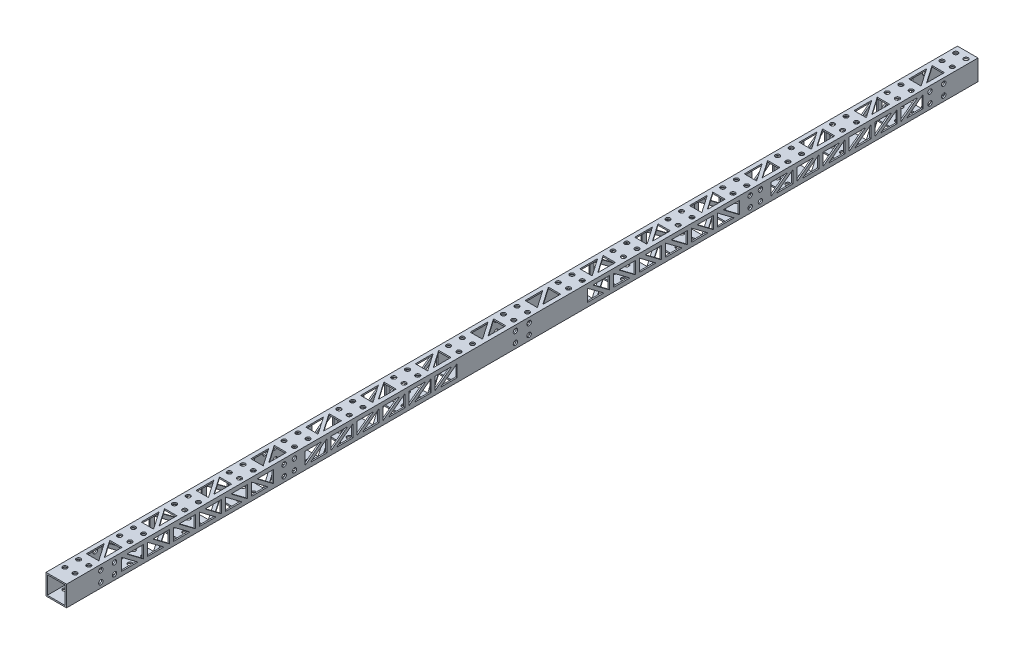
SolidWorks part; units mm, degrees
ref_plane "前视基准面" through (0, 0, 0) normal (0, 0, 1) x (1, 0, 0)
ref_plane "上视基准面" through (0, 0, 0) normal (0, 1, 0) x (1, 0, 0)
ref_plane "右视基准面" through (0, 0, 0) normal (1, 0, 0) x (0, 0, -1)
other "Configuration Table"
sketch "草图1" plane through (0, 0, 0) normal (0, 0, 1) x (1, 0, 0)
  line L1 (0, 0) -> (15, 0)
  line L2 (0, 0) -> (0, -15)
  line L3 (0, -15) -> (15, -15)
  line L4 (15, 0) -> (15, -15)
  dimension "D1" = 15
  dimension "D2" = 15
extrude "拉伸-薄壁1" add sketch "草图1" along normal blind 665 thin
sketch "草图2" plane through (15, 0, 0) normal (1, 0, 0) x (0, 0, -1)
  line L0 (-332.5, 0) -> (-332.5, -15) construction
  line L1 (-665, 0) -> (0, 0) construction
  line L2 (-665, -15) -> (0, -15) construction
  line L3 (-635, 0) -> (-635, -15) construction
  line L4 (-665, -15) -> (-665, 0) construction
  line L5 (-665, -7.5) -> (-635, -7.5) construction
  line L6 (-30, 0) -> (-30, -15) construction
  line L7 (0, -7.5) -> (-30, -7.5) construction
  line L8 (0, -15) -> (0, 0) construction
  line L9 (-635, -7.5) -> (0, -7.5) construction
  line L10 (-502.5, 0) -> (-502.5, -15) construction
  line L11 (-162.5, 0) -> (-162.5, -15) construction
  line L12 (-625, -3) -> (-625, -12)
  line L13 (-625, -12) -> (-613, -12)
  line L14 (-613, -12) -> (-625, -3)
  line L18 (-621, -3) -> (-609, -3)
  line L19 (-609, -3) -> (-609, -12)
  line L20 (-609, -12) -> (-621, -3)
  line L21 (-606, -3) -> (-606, -12)
  line L22 (-594, -12) -> (-606, -3)
  line L23 (-606, -12) -> (-594, -12)
  line L24 (-590, -12) -> (-602, -3)
  line L25 (-602, -3) -> (-590, -3)
  line L26 (-590, -3) -> (-590, -12)
  line L27 (-587, -3) -> (-587, -12)
  line L28 (-575, -12) -> (-587, -3)
  line L29 (-587, -12) -> (-575, -12)
  line L30 (-571, -12) -> (-583, -3)
  line L31 (-583, -3) -> (-571, -3)
  line L32 (-571, -3) -> (-571, -12)
  line L33 (-568, -3) -> (-568, -12)
  line L34 (-556, -12) -> (-568, -3)
  line L35 (-568, -12) -> (-556, -12)
  line L36 (-552, -12) -> (-564, -3)
  line L37 (-564, -3) -> (-552, -3)
  line L38 (-552, -3) -> (-552, -12)
  line L39 (-549, -3) -> (-549, -12)
  line L40 (-537, -12) -> (-549, -3)
  line L41 (-549, -12) -> (-537, -12)
  line L42 (-533, -12) -> (-545, -3)
  line L43 (-545, -3) -> (-533, -3)
  line L44 (-533, -3) -> (-533, -12)
  line L45 (-530, -3) -> (-530, -12)
  line L46 (-518, -12) -> (-530, -3)
  line L47 (-530, -12) -> (-518, -12)
  line L48 (-514, -12) -> (-526, -3)
  line L49 (-526, -3) -> (-514, -3)
  line L50 (-514, -3) -> (-514, -12)
  line L51 (-491, -3) -> (-491, -12)
  line L52 (-479, -3) -> (-491, -3)
  line L53 (-491, -12) -> (-479, -3)
  line L54 (-475, -12) -> (-487, -12)
  line L55 (-487, -12) -> (-475, -3)
  line L56 (-475, -3) -> (-475, -12)
  line L57 (-472, -3) -> (-472, -12)
  line L58 (-460, -3) -> (-472, -3)
  line L59 (-472, -12) -> (-460, -3)
  line L60 (-456, -12) -> (-468, -12)
  line L61 (-468, -12) -> (-456, -3)
  line L62 (-456, -3) -> (-456, -12)
  line L63 (-453, -3) -> (-453, -12)
  line L64 (-441, -3) -> (-453, -3)
  line L65 (-453, -12) -> (-441, -3)
  line L66 (-437, -12) -> (-449, -12)
  line L67 (-449, -12) -> (-437, -3)
  line L68 (-437, -3) -> (-437, -12)
  line L69 (-434, -3) -> (-434, -12)
  line L70 (-422, -3) -> (-434, -3)
  line L71 (-434, -12) -> (-422, -3)
  line L72 (-418, -12) -> (-430, -12)
  line L73 (-430, -12) -> (-418, -3)
  line L74 (-418, -3) -> (-418, -12)
  line L75 (-415, -3) -> (-415, -12)
  line L76 (-403, -3) -> (-415, -3)
  line L77 (-415, -12) -> (-403, -3)
  line L78 (-399, -12) -> (-411, -12)
  line L79 (-411, -12) -> (-399, -3)
  line L80 (-399, -3) -> (-399, -12)
  line L81 (-396, -12) -> (-384, -3)
  line L82 (-396, -3) -> (-396, -12)
  line L83 (-384, -3) -> (-396, -3)
  line L84 (-392, -12) -> (-380, -3)
  line L85 (-380, -12) -> (-392, -12)
  line L86 (-380, -3) -> (-380, -12)
  line L87 (-285, -3) -> (-285, -12)
  line L88 (-285, -12) -> (-273, -12)
  line L89 (-273, -12) -> (-285, -3)
  line L90 (-281, -3) -> (-269, -3)
  line L91 (-269, -3) -> (-269, -12)
  line L92 (-269, -12) -> (-281, -3)
  line L93 (-266, -3) -> (-266, -12)
  line L94 (-254, -12) -> (-266, -3)
  line L95 (-266, -12) -> (-254, -12)
  line L96 (-250, -12) -> (-262, -3)
  line L97 (-262, -3) -> (-250, -3)
  line L98 (-250, -3) -> (-250, -12)
  line L99 (-247, -3) -> (-247, -12)
  line L100 (-235, -12) -> (-247, -3)
  line L101 (-247, -12) -> (-235, -12)
  line L102 (-231, -12) -> (-243, -3)
  line L103 (-243, -3) -> (-231, -3)
  line L104 (-231, -3) -> (-231, -12)
  line L105 (-228, -3) -> (-228, -12)
  line L106 (-216, -12) -> (-228, -3)
  line L107 (-228, -12) -> (-216, -12)
  line L108 (-212, -12) -> (-224, -3)
  line L109 (-224, -3) -> (-212, -3)
  line L110 (-212, -3) -> (-212, -12)
  line L111 (-209, -3) -> (-209, -12)
  line L112 (-197, -12) -> (-209, -3)
  line L113 (-209, -12) -> (-197, -12)
  line L114 (-193, -12) -> (-205, -3)
  line L115 (-205, -3) -> (-193, -3)
  line L116 (-193, -3) -> (-193, -12)
  line L117 (-190, -3) -> (-190, -12)
  line L118 (-178, -12) -> (-190, -3)
  line L119 (-190, -12) -> (-178, -12)
  line L120 (-174, -12) -> (-186, -3)
  line L121 (-186, -3) -> (-174, -3)
  line L122 (-174, -3) -> (-174, -12)
  line L123 (-151, -3) -> (-151, -12)
  line L124 (-139, -3) -> (-151, -3)
  line L125 (-151, -12) -> (-139, -3)
  line L126 (-135, -12) -> (-147, -12)
  line L127 (-147, -12) -> (-135, -3)
  line L128 (-135, -3) -> (-135, -12)
  line L129 (-132, -3) -> (-132, -12)
  line L130 (-120, -3) -> (-132, -3)
  line L131 (-132, -12) -> (-120, -3)
  line L132 (-116, -12) -> (-128, -12)
  line L133 (-128, -12) -> (-116, -3)
  line L134 (-116, -3) -> (-116, -12)
  line L135 (-113, -3) -> (-113, -12)
  line L136 (-101, -3) -> (-113, -3)
  line L137 (-113, -12) -> (-101, -3)
  line L138 (-97, -12) -> (-109, -12)
  line L139 (-109, -12) -> (-97, -3)
  line L140 (-97, -3) -> (-97, -12)
  line L141 (-94, -3) -> (-94, -12)
  line L142 (-82, -3) -> (-94, -3)
  line L143 (-94, -12) -> (-82, -3)
  line L144 (-78, -12) -> (-90, -12)
  line L145 (-90, -12) -> (-78, -3)
  line L146 (-78, -3) -> (-78, -12)
  line L147 (-75, -3) -> (-75, -12)
  line L148 (-63, -3) -> (-75, -3)
  line L149 (-75, -12) -> (-63, -3)
  line L150 (-59, -12) -> (-71, -12)
  line L151 (-71, -12) -> (-59, -3)
  line L152 (-59, -3) -> (-59, -12)
  line L153 (-56, -12) -> (-44, -3)
  line L154 (-56, -3) -> (-56, -12)
  line L155 (-44, -3) -> (-56, -3)
  line L156 (-52, -12) -> (-40, -3)
  line L157 (-40, -12) -> (-52, -12)
  line L158 (-40, -3) -> (-40, -12)
  circle A0 centre (-640, -3.75) radius 1.6
  circle A1 centre (-640, -11.25) radius 1.6
  circle A2 centre (-630, -11.25) radius 1.6
  circle A3 centre (-630, -3.75) radius 1.6
  circle A8 centre (-25, -3.75) radius 1.6
  circle A9 centre (-25, -11.25) radius 1.6
  circle A10 centre (-35, -11.25) radius 1.6
  circle A11 centre (-35, -3.75) radius 1.6
  circle A12 centre (-337.5, -3.75) radius 1.6
  circle A13 centre (-337.5, -11.25) radius 1.6
  circle A14 centre (-327.5, -11.25) radius 1.6
  circle A15 centre (-327.5, -3.75) radius 1.6
  circle A16 centre (-506.25, -3.75) radius 1.6
  circle A17 centre (-506.25, -11.25) radius 1.6
  circle A18 centre (-498.75, -11.25) radius 1.6
  circle A19 centre (-498.75, -3.75) radius 1.6
  circle A20 centre (-166.25, -3.75) radius 1.6
  circle A21 centre (-166.25, -11.25) radius 1.6
  circle A22 centre (-158.75, -11.25) radius 1.6
  circle A23 centre (-158.75, -3.75) radius 1.6
  dimension "D2" = 3.2
  dimension "D6" = 3.2
  dimension "D9" = 3.2
  dimension "D13" = 3.2
  dimension "D1" = 30
  dimension "D3" = 5
  dimension "D4" = 3.75
  dimension "D5" = 30
  dimension "D7" = 3.75
  dimension "D8" = 5
  dimension "D10" = 5
  dimension "D11" = 3.75
  dimension "D12" = 162.5
  dimension "D14" = 3.75
  dimension "D15" = 3.75
  dimension "D16" = 9
  dimension "D17" = 12
  dimension "D18" = 10
  dimension "D19" = 9
  dimension "D20" = 12
  dimension "D21" = 16
  dimension "D23" = 19
  dimension "D22" = 6
extrude "切除-拉伸1" cut sketch "草图2" against normal through all
sketch "草图3" plane through (0, 0, 0) normal (0, 1, 0) x (1, 0, 0)
  line L0 (0, -10) -> (15, -10) construction
  line L1 (0, -665) -> (0, 0) construction
  line L2 (15, -665) -> (15, 0) construction
  line L3 (7.5, 0) -> (7.5, -10) construction
  line L4 (15, 0) -> (0, 0) construction
  line L6 (3, -21.5) -> (12, -21.5)
  line L7 (12, -21.5) -> (12, -34.5)
  line L8 (12, -34.5) -> (3, -21.5)
  line L9 (3, -25.5) -> (3, -38.5)
  line L10 (3, -38.5) -> (12, -38.5)
  line L11 (12, -38.5) -> (3, -25.5)
  line L12 (3, -61.5) -> (12, -61.5)
  line L13 (12, -61.5) -> (12, -74.5)
  line L14 (12, -74.5) -> (3, -61.5)
  line L15 (12, -78.5) -> (3, -65.5)
  line L16 (3, -65.5) -> (3, -78.5)
  line L17 (3, -78.5) -> (12, -78.5)
  line L18 (3, -101.5) -> (12, -101.5)
  line L19 (12, -101.5) -> (12, -114.5)
  line L20 (12, -114.5) -> (3, -101.5)
  line L21 (12, -118.5) -> (3, -105.5)
  line L22 (3, -105.5) -> (3, -118.5)
  line L23 (3, -118.5) -> (12, -118.5)
  line L24 (3, -141.5) -> (12, -141.5)
  line L25 (12, -141.5) -> (12, -154.5)
  line L26 (12, -154.5) -> (3, -141.5)
  line L27 (12, -158.5) -> (3, -145.5)
  line L28 (3, -145.5) -> (3, -158.5)
  line L29 (3, -158.5) -> (12, -158.5)
  line L30 (3, -181.5) -> (12, -181.5)
  line L31 (12, -181.5) -> (12, -194.5)
  line L32 (12, -194.5) -> (3, -181.5)
  line L33 (12, -198.5) -> (3, -185.5)
  line L34 (3, -185.5) -> (3, -198.5)
  line L35 (3, -198.5) -> (12, -198.5)
  line L36 (3, -221.5) -> (12, -221.5)
  line L37 (12, -221.5) -> (12, -234.5)
  line L38 (12, -234.5) -> (3, -221.5)
  line L39 (12, -238.5) -> (3, -225.5)
  line L40 (3, -225.5) -> (3, -238.5)
  line L41 (3, -238.5) -> (12, -238.5)
  line L42 (3, -261.5) -> (12, -261.5)
  line L43 (12, -261.5) -> (12, -274.5)
  line L44 (12, -274.5) -> (3, -261.5)
  line L45 (12, -278.5) -> (3, -265.5)
  line L46 (3, -265.5) -> (3, -278.5)
  line L47 (3, -278.5) -> (12, -278.5)
  line L48 (3, -301.5) -> (12, -301.5)
  line L49 (12, -301.5) -> (12, -314.5)
  line L50 (12, -314.5) -> (3, -301.5)
  line L51 (12, -318.5) -> (3, -305.5)
  line L52 (3, -305.5) -> (3, -318.5)
  line L53 (3, -318.5) -> (12, -318.5)
  line L54 (3, -341.5) -> (12, -341.5)
  line L55 (12, -341.5) -> (12, -354.5)
  line L56 (12, -354.5) -> (3, -341.5)
  line L57 (12, -358.5) -> (3, -345.5)
  line L58 (3, -345.5) -> (3, -358.5)
  line L59 (3, -358.5) -> (12, -358.5)
  line L60 (3, -381.5) -> (12, -381.5)
  line L61 (12, -381.5) -> (12, -394.5)
  line L62 (12, -394.5) -> (3, -381.5)
  line L63 (12, -398.5) -> (3, -385.5)
  line L64 (3, -385.5) -> (3, -398.5)
  line L65 (3, -398.5) -> (12, -398.5)
  line L66 (3, -421.5) -> (12, -421.5)
  line L67 (12, -421.5) -> (12, -434.5)
  line L68 (12, -434.5) -> (3, -421.5)
  line L69 (12, -438.5) -> (3, -425.5)
  line L70 (3, -425.5) -> (3, -438.5)
  line L71 (3, -438.5) -> (12, -438.5)
  line L72 (3, -461.5) -> (12, -461.5)
  line L73 (12, -461.5) -> (12, -474.5)
  line L74 (12, -474.5) -> (3, -461.5)
  line L75 (12, -478.5) -> (3, -465.5)
  line L76 (3, -465.5) -> (3, -478.5)
  line L77 (3, -478.5) -> (12, -478.5)
  line L78 (3, -501.5) -> (12, -501.5)
  line L79 (12, -501.5) -> (12, -514.5)
  line L80 (12, -514.5) -> (3, -501.5)
  line L81 (12, -518.5) -> (3, -505.5)
  line L82 (3, -505.5) -> (3, -518.5)
  line L83 (3, -518.5) -> (12, -518.5)
  line L84 (3, -541.5) -> (12, -541.5)
  line L85 (12, -541.5) -> (12, -554.5)
  line L86 (12, -554.5) -> (3, -541.5)
  line L87 (12, -558.5) -> (3, -545.5)
  line L88 (3, -545.5) -> (3, -558.5)
  line L89 (3, -558.5) -> (12, -558.5)
  line L90 (3, -581.5) -> (12, -581.5)
  line L91 (12, -581.5) -> (12, -594.5)
  line L92 (12, -594.5) -> (3, -581.5)
  line L93 (12, -598.5) -> (3, -585.5)
  line L94 (3, -585.5) -> (3, -598.5)
  line L95 (3, -598.5) -> (12, -598.5)
  line L96 (3, -621.5) -> (12, -621.5)
  line L97 (12, -621.5) -> (12, -634.5)
  line L98 (12, -634.5) -> (3, -621.5)
  line L99 (12, -638.5) -> (3, -625.5)
  line L100 (3, -625.5) -> (3, -638.5)
  line L101 (3, -638.5) -> (12, -638.5)
  circle A0 centre (3.75, -5) radius 1.6
  circle A1 centre (11.25, -5) radius 1.6
  circle A2 centre (11.25, -15) radius 1.6
  circle A3 centre (3.75, -15) radius 1.6
  circle A4 centre (3.75, -45) radius 1.6
  circle A5 centre (11.25, -45) radius 1.6
  circle A6 centre (11.25, -55) radius 1.6
  circle A7 centre (3.75, -55) radius 1.6
  circle A8 centre (3.75, -85) radius 1.6
  circle A9 centre (11.25, -85) radius 1.6
  circle A10 centre (11.25, -95) radius 1.6
  circle A11 centre (3.75, -95) radius 1.6
  circle A12 centre (3.75, -125) radius 1.6
  circle A13 centre (11.25, -125) radius 1.6
  circle A14 centre (11.25, -135) radius 1.6
  circle A15 centre (3.75, -135) radius 1.6
  circle A16 centre (3.75, -165) radius 1.6
  circle A17 centre (11.25, -165) radius 1.6
  circle A18 centre (11.25, -175) radius 1.6
  circle A19 centre (3.75, -175) radius 1.6
  circle A20 centre (3.75, -205) radius 1.6
  circle A21 centre (11.25, -205) radius 1.6
  circle A22 centre (11.25, -215) radius 1.6
  circle A23 centre (3.75, -215) radius 1.6
  circle A24 centre (3.75, -245) radius 1.6
  circle A25 centre (11.25, -245) radius 1.6
  circle A26 centre (11.25, -255) radius 1.6
  circle A27 centre (3.75, -255) radius 1.6
  circle A28 centre (3.75, -285) radius 1.6
  circle A29 centre (11.25, -285) radius 1.6
  circle A30 centre (11.25, -295) radius 1.6
  circle A31 centre (3.75, -295) radius 1.6
  circle A32 centre (3.75, -325) radius 1.6
  circle A33 centre (11.25, -325) radius 1.6
  circle A34 centre (11.25, -335) radius 1.6
  circle A35 centre (3.75, -335) radius 1.6
  circle A36 centre (3.75, -365) radius 1.6
  circle A37 centre (11.25, -365) radius 1.6
  circle A38 centre (11.25, -375) radius 1.6
  circle A39 centre (3.75, -375) radius 1.6
  circle A40 centre (3.75, -405) radius 1.6
  circle A41 centre (11.25, -405) radius 1.6
  circle A42 centre (11.25, -415) radius 1.6
  circle A43 centre (3.75, -415) radius 1.6
  circle A44 centre (3.75, -445) radius 1.6
  circle A45 centre (11.25, -445) radius 1.6
  circle A46 centre (11.25, -455) radius 1.6
  circle A47 centre (3.75, -455) radius 1.6
  circle A48 centre (3.75, -485) radius 1.6
  circle A49 centre (11.25, -485) radius 1.6
  circle A50 centre (11.25, -495) radius 1.6
  circle A51 centre (3.75, -495) radius 1.6
  circle A52 centre (3.75, -525) radius 1.6
  circle A53 centre (11.25, -525) radius 1.6
  circle A54 centre (11.25, -535) radius 1.6
  circle A55 centre (3.75, -535) radius 1.6
  circle A56 centre (3.75, -565) radius 1.6
  circle A57 centre (11.25, -565) radius 1.6
  circle A58 centre (11.25, -575) radius 1.6
  circle A59 centre (3.75, -575) radius 1.6
  circle A60 centre (3.75, -605) radius 1.6
  circle A61 centre (11.25, -605) radius 1.6
  circle A62 centre (11.25, -615) radius 1.6
  circle A63 centre (3.75, -615) radius 1.6
  circle A64 centre (3.75, -645) radius 1.6
  circle A65 centre (11.25, -645) radius 1.6
  circle A66 centre (11.25, -655) radius 1.6
  circle A67 centre (3.75, -655) radius 1.6
  dimension "D1" = 3.2
  dimension "D2" = 3.75
  dimension "D3" = 5
  dimension "D4" = 10
  dimension "D6" = 40
  dimension "D7" = 13
  dimension "D8" = 9
  dimension "D9" = 13
  dimension "D10" = 9
  dimension "D11" = 11.5
  dimension "D12" = 6.5
  dimension "D14" = 40
  dimension "D5" = 17
  dimension "D13" = 16
extrude "切除-拉伸2" cut sketch "草图3" against normal through all
